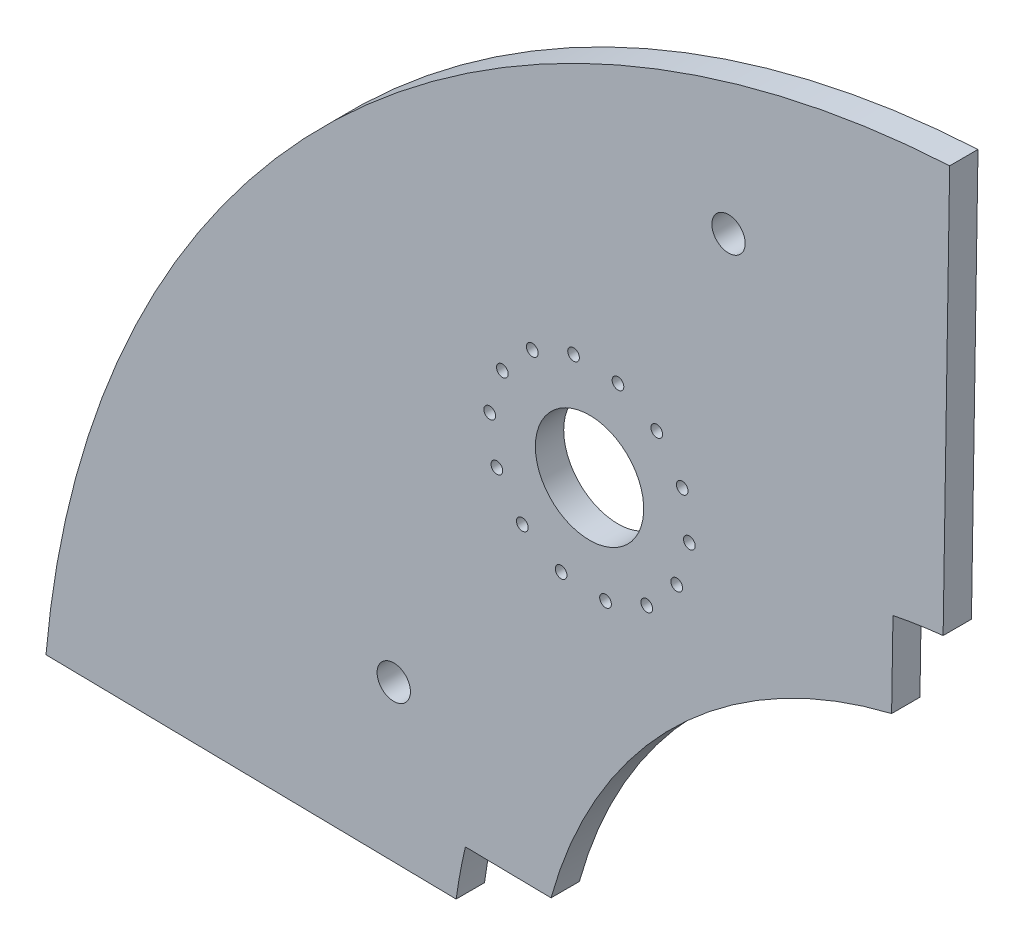
SolidWorks part; units mm, degrees
ref_plane "Front Plane" through (0, 0, 0) normal (0, 0, 1) x (1, 0, 0)
ref_plane "Top Plane" through (0, 0, 0) normal (0, 1, 0) x (1, 0, 0)
ref_plane "Right Plane" through (0, 0, 0) normal (1, 0, 0) x (0, 0, -1)
sketch "Sketch1" plane through (0, 0, 0) normal (0, 0, 1) x (0.9999, -0.016, 0)
  line L0 (-2.9977, 37.0671) -> (-2.9977, 32.5309)
  line L1 (-23.7105, 11.8181) -> (-28.2467, 11.8181)
  line L2 (-2.9977, 32.5309) -> (-2.9977, 31.9289)
  line L3 (0.0023, 62.1788) -> (0.0023, 37.5747)
  line L4 (-23.7105, 11.8181) -> (-23.1086, 11.8181)
  line L6 (-53.3584, 8.8181) -> (-28.7544, 8.8181)
  arc A0 (-2.9977, 31.9289) -> (-23.1086, 11.8181) centre (4.0023, 4.8181) ccw
  arc A2 (0.0023, 62.1788) -> (-53.3584, 8.8181) centre (4.0023, 4.8181) ccw
  arc A5 (-28.2467, 11.8181) -> (-28.7544, 8.8181) centre (4.0023, 4.8181) ccw
  arc A6 (0.0023, 37.5747) -> (-2.9977, 37.0671) centre (4.0023, 4.8181) ccw
  circle A47 centre (-19.5516, 40.6141) radius 0.35
  circle A48 centre (-17.2041, 39.3416) radius 0.35
  circle A49 centre (-15.6411, 37.1765) radius 0.35
  circle A50 centre (-15.1724, 34.5477) radius 0.35
  circle A51 centre (-15.8906, 31.9759) radius 0.35
  circle A52 centre (-17.6536, 29.9704) radius 0.35
  circle A53 centre (-20.1121, 28.9284) radius 0.35
  circle A54 centre (-22.7793, 29.0563) radius 0.35
  circle A55 centre (-25.1269, 30.3289) radius 0.35
  circle A56 centre (-26.6898, 32.4939) radius 0.35
  circle A57 centre (-27.1586, 35.1227) radius 0.35
  circle A58 centre (-26.4403, 37.6945) radius 0.35
  circle A59 centre (-24.6774, 39.7001) radius 0.35
  circle A60 centre (-22.2188, 40.742) radius 0.35
  circle A61 centre (-21.1655, 34.8352) radius 3.25
extrude "Boss-Extrude1" add sketch "Sketch1" along normal blind 1.7
extrude "Cut-Extrude7" cut sketch "Sketch8" against normal blind 8 and the other way through all
sketch "Sketch8" plane through (0, 0, -51.287) normal (0, 0, 1) x (0.9999, -0.016, 0)
  circle A0 centre (-13.0987, 51.8027) radius 1
  circle A1 centre (21.1033, 51.8027) radius 1
  circle A2 centre (40.6503, 18.1569) radius 1
  circle A3 centre (55.5443, -5.1203) radius 1
  circle A4 centre (20.5093, -31.747) radius 1
  circle A5 centre (-12.5047, -31.747) radius 1
  circle A6 centre (-47.5397, -5.1203) radius 1
  circle A7 centre (-32.6457, 18.1569) radius 1
